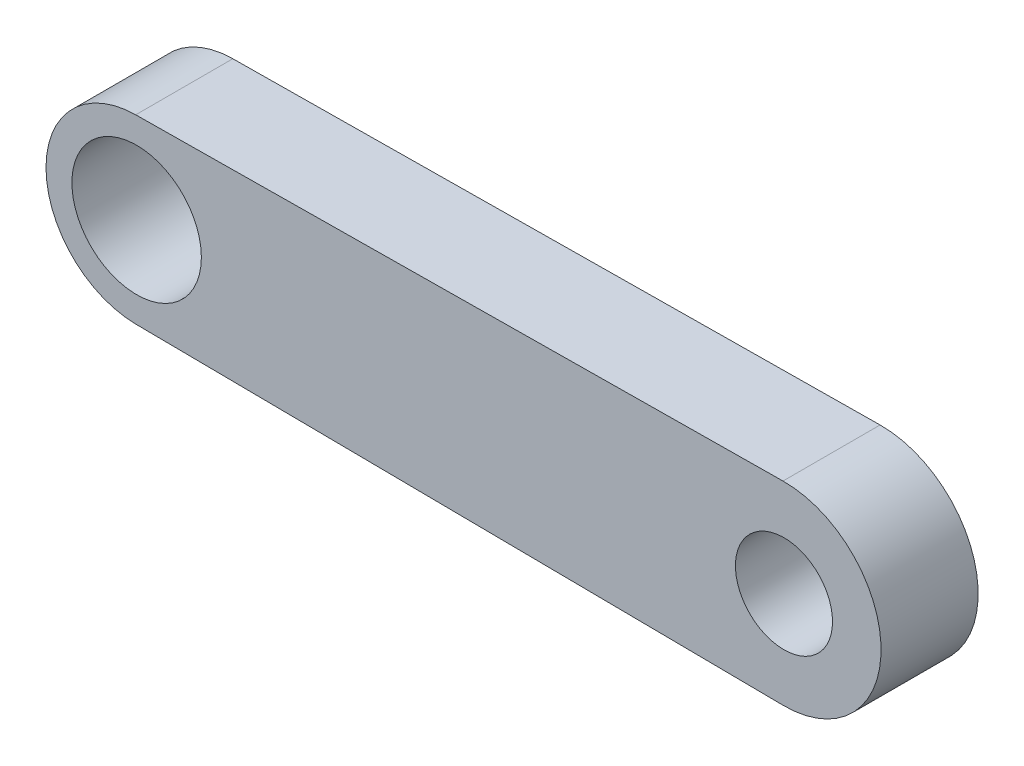
SolidWorks part; units mm, degrees
ref_plane "Plan de face" through (0, 0, 0) normal (0, 0, 1) x (1, 0, 0)
ref_plane "Plan de dessus" through (0, 0, 0) normal (0, 1, 0) x (1, 0, 0)
ref_plane "Plan de droite" through (0, 0, 0) normal (1, 0, 0) x (0, 0, -1)
sketch "Esquisse1" plane through (0, 0, 0) normal (0, 0, 1) x (1, 0, 0)
  line L0 (-0.028, 2.7999) -> (19.97, 2.9998)
  line L3 (19.97, -2.9998) -> (-0.028, -2.7999)
  line L4 (1.3, 0.3) -> (2.7, -0.3) construction
  line L5 (1.3, 0.3) -> (2.7, 0.3) construction
  line L6 (1.3, 0.3) -> (1.3, -0.3) construction
  line L7 (1.3, -0.3) -> (2.7, -0.3) construction
  line L8 (2.7, 0.3) -> (2.7, -0.3) construction
  arc A2 (-0.028, 2.7999) -> (-0.028, -2.7999) centre (0, 0) ccw
  arc A3 (19.97, 2.9998) -> (19.97, -2.9998) centre (20, 0) cw
  circle A5 centre (20, 0) radius 1.5
  circle A6 centre (0, 0) radius 2
  point P13 (1.3, 0)
  point P14 (2, 0)
  dimension "D1" = 0.6
  dimension "D2" = 2.8
  dimension "D3" = 3
  dimension "D5" = 3
  dimension "D6" = 4
  dimension "D4" = 20
  dimension "D7" = 1.3
extrude "Boss.-Extru.1" add sketch "Esquisse1" along normal blind 3 contours A3 L0 A2 L3 A6 A5 | L6 L5 L8 L7
